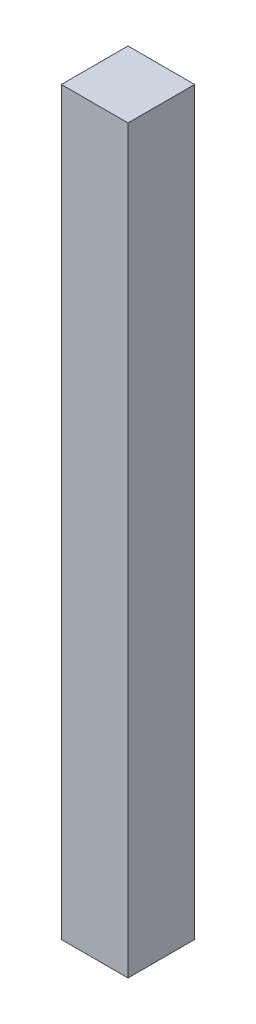
SolidWorks part; units mm, degrees
ref_plane "Front Plane" through (0, 0, 0) normal (0, 0, 1) x (1, 0, 0)
ref_plane "Top Plane" through (0, 0, 0) normal (0, 1, 0) x (1, 0, 0)
ref_plane "Right Plane" through (0, 0, 0) normal (1, 0, 0) x (0, 0, -1)
other "Configuration Table"
sketch "Sketch1" plane through (0, 0, 0) normal (0, 0, 1) x (1, 0, 0)
  line L1 (654, 436) -> (672, 436)
  line L2 (654, 436) -> (654, 636)
  line L3 (654, 636) -> (672, 636)
  line L4 (672, 436) -> (672, 636)
extrude "STORE_klape_kaset_kati_gazli_amortisor_2_1" add sketch "Sketch1" against normal blind 18 from offset 12 separate body
